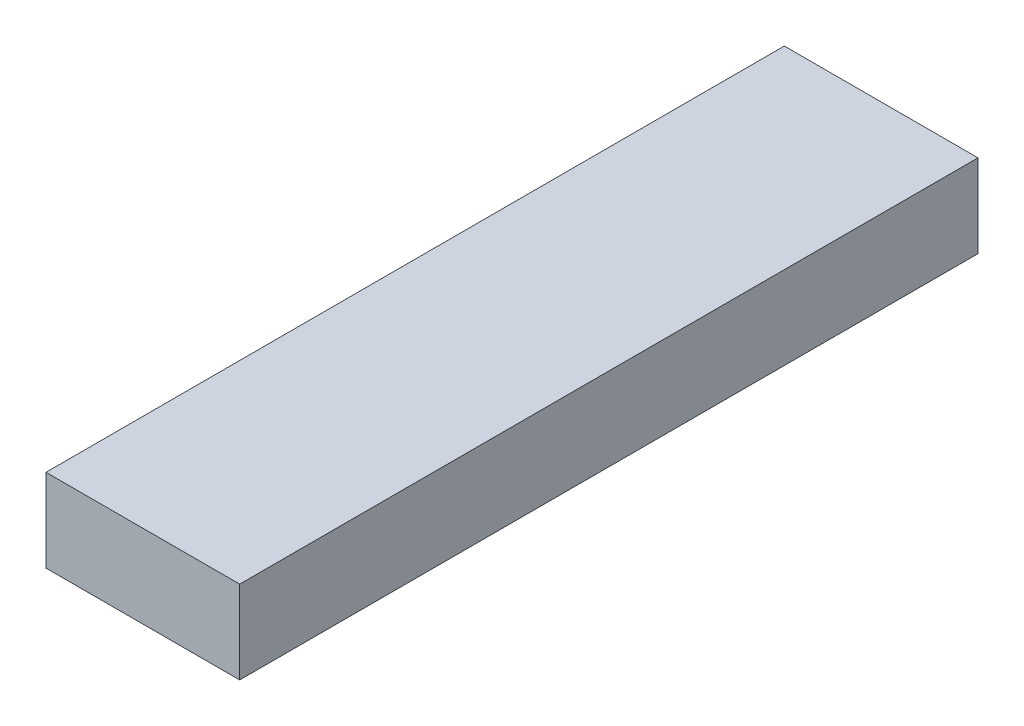
SolidWorks part; units mm, degrees
material "Pine"
ref_plane "Front Plane" through (0, 0, 0) normal (0, 0, 1) x (1, 0, 0)
ref_plane "Top Plane" through (0, 0, 0) normal (0, 1, 0) x (1, 0, 0)
ref_plane "Right Plane" through (0, 0, 0) normal (1, 0, 0) x (0, 0, -1)
sketch "Sketch1" plane through (0, 0, 0) normal (0, 0, 1) x (1, 0, 0)
  line L1 (-44.45, -19.05) -> (44.45, -19.05)
  line L2 (-44.45, -19.05) -> (-44.45, 19.05)
  line L3 (-44.45, 19.05) -> (44.45, 19.05)
  line L4 (44.45, -19.05) -> (44.45, 19.05)
  line L5 (-44.45, -19.05) -> (44.45, 19.05) construction
  line L6 (-44.45, 19.05) -> (44.45, -19.05) construction
  point P0 (0, 0)
  dimension "D1" = 88.9
  dimension "D2" = 38.1
extrude "Boss-Extrude1" add sketch "Sketch1" along normal blind 338.9
